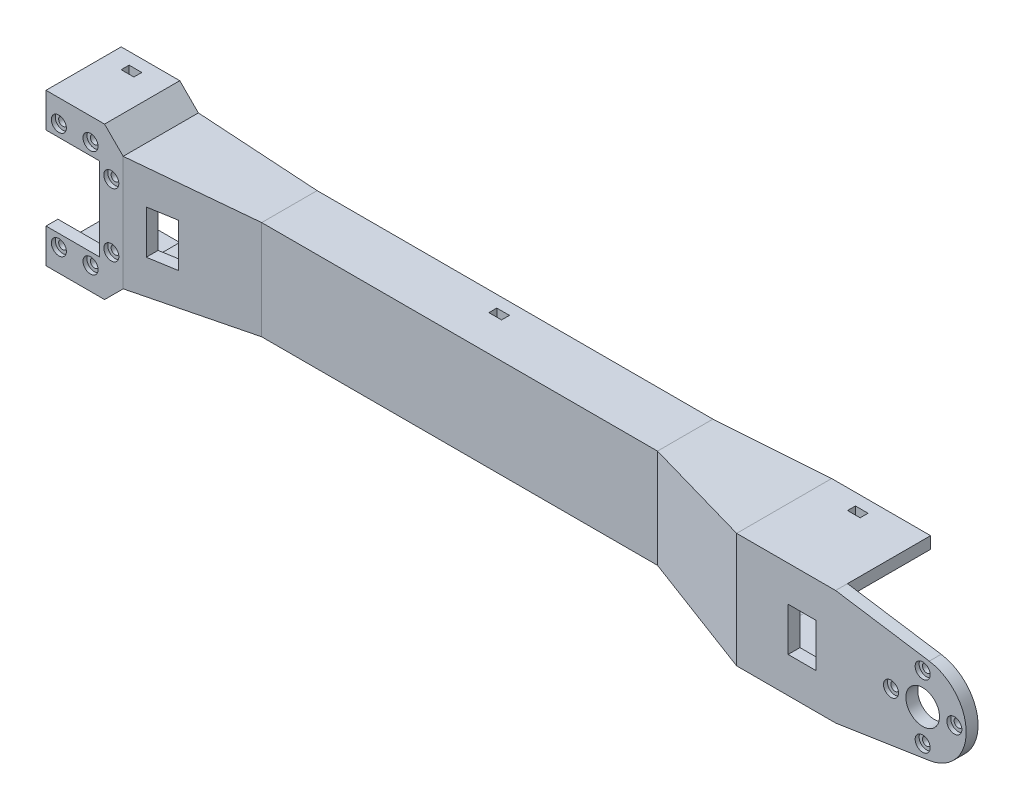
SolidWorks part; units mm, degrees
ref_plane "Front Plane" through (0, 0, 0) normal (0, 0, 1) x (1, 0, 0)
ref_plane "Top Plane" through (0, 0, 0) normal (0, 1, 0) x (1, 0, 0)
ref_plane "Right Plane" through (0, 0, 0) normal (1, 0, 0) x (0, 0, -1)
sketch "Sketch1" plane through (0, 0, 0) normal (0, 0, 1) x (1, 0, 0)
  line L0 (25, 29) -> (48.6663, 25.3731)
  line L1 (0, 0) -> (25, 0)
  line L2 (0, 0) -> (0, 29)
  line L3 (0, 29) -> (25, 29)
  line L5 (25, 0) -> (48.6663, 3.6269)
  line L6 (0, 14.5) -> (81.3972, 14.5) construction
  arc A0 (48.6663, 3.6269) -> (48.6663, 25.3731) centre (47, 14.5) ccw
  dimension "D1" = 22
  dimension "D2" = 29
  dimension "D3" = 22
  dimension "D4" = 25
extrude "Boss-Extrude1" add sketch "Sketch1" against normal blind 3
sketch "Sketch2" plane through (0, 0, 0) normal (0, 0, 1) x (1, 0, 0)
  line L0 (47, 22.5) -> (47, 6.5) construction
  line L1 (39, 14.5) -> (55, 14.5) construction
  circle A0 centre (47, 14.5) radius 4.25
  circle A1 centre (47, 22.5) radius 1.05
  circle A2 centre (55, 14.5) radius 1.05
  circle A3 centre (47, 6.5) radius 1.05
  circle A4 centre (39, 14.5) radius 1.05
  dimension "D1" = 8.5
  dimension "D3" = 2.1
  dimension "D2" = 16
extrude "Cut-Extrude1" cut sketch "Sketch2" against normal up to next
sketch "Sketch3" plane through (0, 0, 0) normal (0, 0, 1) x (1, 0, 0)
  circle A0 centre (47, 22.5) radius 1.9
  circle A1 centre (55, 14.5) radius 1.9
  circle A2 centre (47, 6.5) radius 1.9
  circle A3 centre (39, 14.5) radius 1.9
  dimension "D1" = 3.8
extrude "Cut-Extrude2" cut sketch "Sketch3" against normal blind 1
sketch "Sketch4" plane through (0, 29, 0) normal (0, 1, 0) x (1, 0, 0)
  line L0 (0, 3) -> (0, 0)
  line L1 (0, 0) -> (-30, 10)
  line L2 (-30, 10) -> (-130, 10)
  line L3 (-130, 10) -> (-160, 5)
  line L4 (-160, 5) -> (-160, 8)
  line L5 (-160, 8) -> (-130, 13)
  line L6 (-130, 13) -> (-30, 13)
  line L7 (-30, 13) -> (0, 3)
  line L8 (25, 0) -> (0, 0) construction
  dimension "D1" = 5
  dimension "D2" = 10
  dimension "D3" = 3
  dimension "D4" = 30
  dimension "D5" = 30
  dimension "D6" = 160
extrude "Boss-Extrude2" add sketch "Sketch4" against normal up to surface (29 mm away) up to face at (12.5, 0, -1.5)
ref_plane "Plane1" through (0, 0, -5) normal (0, 0, 1) x (1, 0, 0)
sketch "Sketch7" plane through (0, 0, -5) normal (0, 0, 1) x (1, 0, 0)
  line L0 (-160, 29) -> (-164.7, 33.7)
  line L1 (-160, 0) -> (-160, 29) construction
  line L2 (-164.7, 33.7) -> (-179.5, 33.7)
  line L3 (-179.5, 33.7) -> (-179.5, 25)
  line L4 (-179.5, 25) -> (-166, 25)
  line L5 (-166, 25) -> (-166, 4)
  line L6 (-166, 4) -> (-179.5, 4)
  line L7 (-179.5, 4) -> (-179.5, -4.7)
  line L8 (-179.5, -4.7) -> (-164.7, -4.7)
  line L9 (-164.7, -4.7) -> (-160, 0)
  line L10 (-160, 0) -> (-160, 29)
  line L11 (-166, 14.5) -> (-160, 14.5) construction
  point P4 (-160, 14.5)
  dimension "D1" = 8.7
  dimension "D2" = 6
  dimension "D3" = 13.5
  dimension "D4" = 45
  dimension "D6" = 38.4
extrude "Boss-Extrude4" add sketch "Sketch7" against normal blind 3
sketch "Sketch8" plane through (0, 0, -5) normal (0, 0, 1) x (1, 0, 0)
  line L0 (-176.25, 28) -> (-168.25, 28) construction
  line L1 (-168.25, 28) -> (-163, 22.5) construction
  line L2 (-163, 22.5) -> (-163, 6.5) construction
  line L3 (-163, 6.5) -> (-168.25, 1) construction
  line L4 (-168.25, 1) -> (-176.25, 1) construction
  line L6 (-166, 14.5) -> (-163, 14.5) construction
  line L7 (-166, 25) -> (-166, 4) construction
  circle A0 centre (-176.25, 28) radius 1.05
  circle A1 centre (-168.25, 28) radius 1.05
  circle A2 centre (-163, 22.5) radius 1.05
  circle A3 centre (-163, 6.5) radius 1.05
  circle A4 centre (-168.25, 1) radius 1.05
  circle A5 centre (-176.25, 1) radius 1.05
  dimension "D7" = 2.1
  dimension "D1" = 3
  dimension "D2" = 5.25
  dimension "D3" = 5.5
  dimension "D4" = 16
  dimension "D5" = 8
  dimension "D6" = 5.5
extrude "Cut-Extrude3" cut sketch "Sketch8" against normal up to next
sketch "Sketch9" plane through (0, 0, -5) normal (0, 0, 1) x (1, 0, 0)
  circle A0 centre (-176.25, 28) radius 1.9
  circle A1 centre (-168.25, 28) radius 1.9
  circle A2 centre (-163, 22.5) radius 1.9
  circle A3 centre (-163, 6.5) radius 1.9
  circle A4 centre (-168.25, 1) radius 1.9
  circle A5 centre (-176.25, 1) radius 1.9
  dimension "D1" = 3.8
extrude "Cut-Extrude4" cut sketch "Sketch9" against normal blind 1
sketch "Sketch11" plane through (0, 0, 0) normal (0, 0, 1) x (1, 0, 0)
  line L0 (0, 0) -> (-30, 2)
  line L1 (-30, 0) -> (-30, 29) construction
  line L2 (-30, 2) -> (-130, 2)
  line L3 (-130, 0) -> (-130, 29) construction
  line L4 (-130, 2) -> (-160, 0)
  line L5 (-160, 0) -> (-160, 29) construction
  line L6 (-160, 0) -> (0, 0)
  line L7 (0, 29) -> (-30, 27)
  line L8 (-30, 27) -> (-130, 27)
  line L9 (-130, 27) -> (-160, 29)
  line L10 (-160, 29) -> (0, 29)
  dimension "D1" = 25
extrude "Cut-Extrude5" cut sketch "Sketch11" against normal up to surface (13 mm away) up to face at (-80, 14.5, -13)
ref_plane "Plane2" through (0, 0, -24) normal (0, 0, 1) x (1, 0, 0)
sketch "Sketch14" plane through (0, 0, -24) normal (0, 0, 1) x (1, 0, 0)
  line L0 (-179.5, 33.7) -> (-179.5, 30.7)
  line L1 (-179.5, 33.7) -> (-179.5, 25) construction
  line L2 (-179.5, 30.7) -> (-164.7, 30.7)
  line L3 (-164.7, 30.7) -> (-160, 26)
  line L4 (-160, 0) -> (-160, 29) construction
  line L5 (-160, 26) -> (-130, 24)
  line L6 (-130, 2) -> (-130, 27) construction
  line L7 (-130, 24) -> (-30, 24)
  line L8 (-30, 2) -> (-30, 27) construction
  line L9 (-30, 24) -> (0, 26)
  line L10 (0, 29) -> (0, 0) construction
  line L11 (0, 26) -> (25, 26)
  line L12 (25, 26) -> (25, 29)
  line L13 (25, 29) -> (0, 29) construction
  line L14 (25, 29) -> (0, 29)
  line L15 (0, 29) -> (-30, 27)
  line L16 (-30, 27) -> (-130, 27)
  line L17 (-130, 27) -> (-160, 29)
  line L18 (-160, 29) -> (-164.7, 33.7)
  line L19 (-164.7, 33.7) -> (-179.5, 33.7)
  dimension "D1" = 3
  dimension "D2" = 3
  dimension "D3" = 25
extrude "Boss-Extrude8" add sketch "Sketch14" along normal up to body separate body
ref_plane "Plane3" through (0, 14.5, 0) normal (0, 1, 0) x (1, 0, 0)
mirror "Mirror1" about plane through (0, 14.5, 0) normal (0, 1, 0) of "Boss-Extrude8"
sketch "Sketch16" plane through (0, 33.7, 0) normal (0, 1, 0) x (1, 0, 0)
  line L0 (-27.1688, 24) -> (27.1688, 24) construction
  line L1 (-174.5, 21) -> (-171.3, 21)
  line L2 (-174.5, 21) -> (-174.5, 19)
  line L3 (-174.5, 19) -> (-171.3, 19)
  line L4 (-171.3, 21) -> (-171.3, 19)
  line L5 (-179.5, 24) -> (-179.5, 5) construction
  line L6 (-30, 24) -> (-130, 24) construction
  line L7 (-81.6, 21) -> (-78.4, 21)
  line L8 (-81.6, 21) -> (-81.6, 19)
  line L9 (-81.6, 19) -> (-78.4, 19)
  line L10 (-78.4, 21) -> (-78.4, 19)
  line L12 (-80, 10) -> (-80, 24) construction
  line L13 (9, 19) -> (12.2, 19)
  line L14 (9, 19) -> (9, 21)
  line L15 (9, 21) -> (12.2, 21)
  line L16 (12.2, 19) -> (12.2, 21)
  line L17 (0, 24) -> (0, 0) construction
  line L18 (-130, 10) -> (-30, 10) construction
  point P14 (-80, 19)
  dimension "D1" = 3.2
  dimension "D2" = 2
  dimension "D3" = 3
  dimension "D4" = 5
  dimension "D5" = 3.2
  dimension "D6" = 2
  dimension "D7" = 3
  dimension "D9" = 3.2
  dimension "D10" = 2
  dimension "D11" = 3
  dimension "D12" = 9
extrude "Cut-Extrude6" cut sketch "Sketch16" against normal through all
sketch "Sketch17" plane through (0, 0, 0) normal (0, 0, 1) x (1, 0, 0)
  line L0 (47, 14.5) -> (-100.5533, 14.5) construction
  line L1 (-160, 0) -> (-160, 29) construction
  line L2 (-155, 9) -> (-148, 9)
  line L3 (-155, 9) -> (-155, 20)
  line L4 (-155, 20) -> (-148, 20)
  line L5 (-148, 9) -> (-148, 20)
  line L6 (-155, 9) -> (-148, 20) construction
  line L7 (-155, 20) -> (-148, 9) construction
  line L8 (13, 9) -> (20, 9)
  line L9 (13, 9) -> (13, 20)
  line L10 (13, 20) -> (20, 20)
  line L11 (20, 9) -> (20, 20)
  line L12 (13, 9) -> (20, 20) construction
  line L13 (13, 20) -> (20, 9) construction
  point P3 (-151.5, 14.5)
  point P8 (16.5, 14.5)
  dimension "D1" = 7
  dimension "D2" = 11
  dimension "D3" = 5
  dimension "D4" = 5
extrude "Cut-Extrude7" cut sketch "Sketch17" against normal up to next
